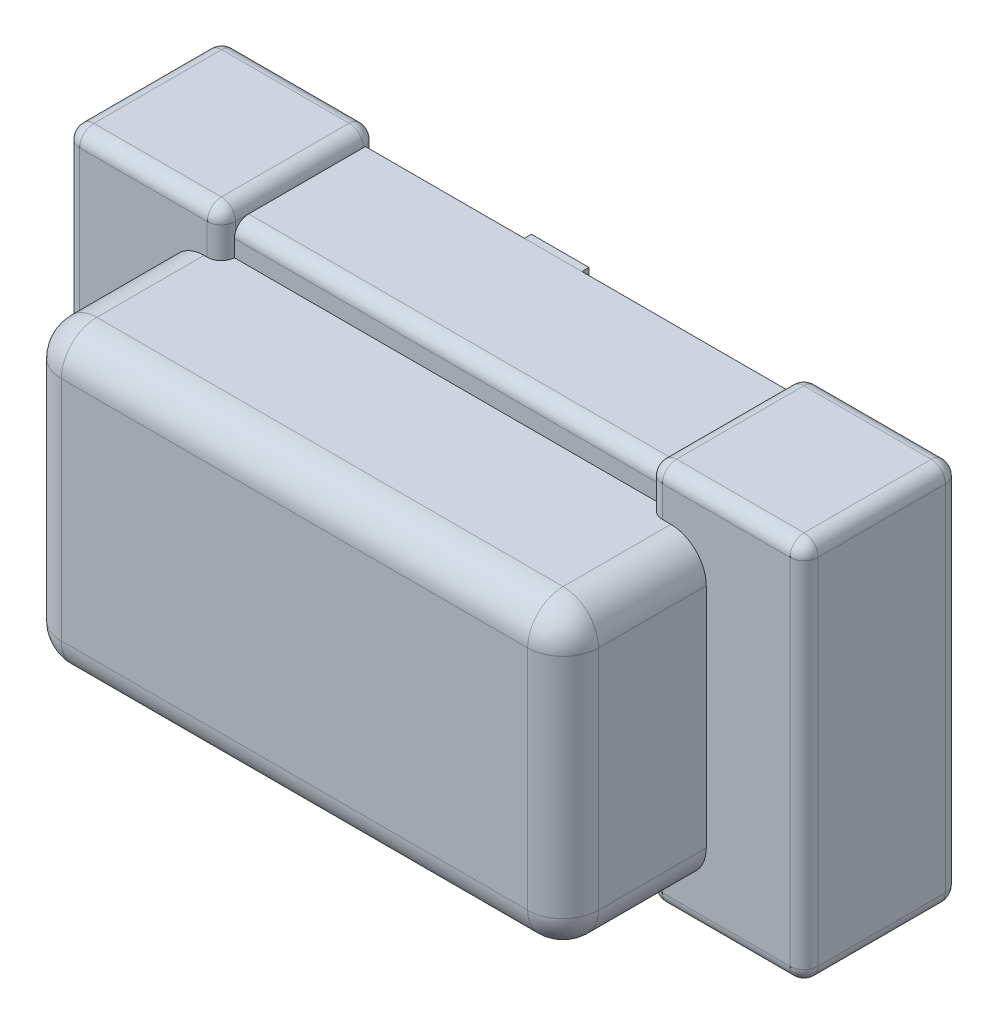
SolidWorks part; units mm, degrees
other "body"
other "bottom"
other "left"
other "right"
other "light"
ref_plane "Front Plane" through (0, 0, 0) normal (0, 0, 1) x (1, 0, 0)
ref_plane "Top Plane" through (0, 0, 0) normal (0, 1, 0) x (1, 0, 0)
ref_plane "Right Plane" through (0, 0, 0) normal (1, 0, 0) x (0, 0, -1)
sketch "Sketch3" plane through (0, 0, 0) normal (0, 0, 1) x (1, 0, 0)
  line L1 (0, 0) -> (1, 0)
  line L2 (0, 0) -> (0, 0.5)
  line L3 (0, 0.5) -> (1, 0.5)
  line L4 (1, 0) -> (1, 0.5)
  dimension "D1" = 1
  dimension "D2" = 0.5
extrude "Boss-Extrude1" add sketch "Sketch3" along normal blind 0.1848
sketch "Sketch4" plane through (0, 0, 0) normal (0, 1, 0) x (1, 0, 0)
  line L1 (-0.022, -0.2033) -> (0.198, -0.2033)
  line L2 (-0.022, -0.2033) -> (-0.022, 0.017)
  line L3 (-0.022, 0.017) -> (0.198, 0.017)
  line L4 (0.198, -0.2033) -> (0.198, 0.017)
  line L5 (1.02, -0.2026) -> (0.8, -0.2026)
  line L6 (1.02, -0.2026) -> (1.02, 0.017)
  line L7 (1.02, 0.017) -> (0.8, 0.017)
  line L8 (0.8, -0.2026) -> (0.8, 0.017)
  dimension "D1" = 0.22
  dimension "D2" = 0.22
  dimension "D3" = 0.2203
  dimension "D4" = 0.2196
sketch "Sketch6" plane through (0, 0, 0) normal (0, 0, -1) x (-1, 0, 0)
  line L0 (0, 0) -> (-1, 0) construction
  line L1 (-0.4224, 0) -> (-0.5037, 0)
  line L2 (-0.4224, 0) -> (-0.4224, 0.5)
  line L3 (-0.4224, 0.5) -> (-0.5037, 0.5)
  line L4 (-0.5037, 0) -> (-0.5037, 0.5)
  line L5 (-1, 0.5) -> (0, 0.5) construction
  line L7 (-0.5037, 0.1333) -> (-0.5755, 0.1333)
  line L8 (-0.5037, 0.1333) -> (-0.5037, 0.3475)
  line L9 (-0.5037, 0.3475) -> (-0.5755, 0.3475)
  line L10 (-0.5755, 0.1333) -> (-0.5755, 0.3475)
  line M2 (-1, 0) -> (0, 0)
  line M4 (0, 0.5) -> (-1, 0.5)
extrude "Boss-Extrude5" add sketch "Sketch6" along normal blind 0.01 separate body contours L4 L2 M2 M4 | L10 L7 L4 L9
extrude "Boss-Extrude9" add sketch "Sketch4" along normal blind 0.52 and the other way blind 0.02 separate body
sketch "Sketch7" plane through (0, 0, 0.1848) normal (0, 0, 1) x (1, 0, 0)
  line L1 (0.882, 0.0356) -> (0.1235, 0.0356)
  line L2 (0.882, 0.0356) -> (0.882, 0.4563)
  line L3 (0.882, 0.4563) -> (0.1235, 0.4563)
  line L4 (0.1235, 0.0356) -> (0.1235, 0.4563)
extrude "Boss-Extrude10" add sketch "Sketch7" along normal blind 0.22 separate body
fillet "Fillet4" radius 0.05 8 edges at (0.882, 0.0356, 0.2948) (0.1235, 0.0356, 0.2948) (0.5027, 0.4563, 0.4048) (0.882, 0.4563, 0.2948) (0.1235, 0.4563, 0.2948) (0.1235, 0.246, 0.4048) (0.882, 0.246, 0.4048) (0.5027, 0.0356, 0.4048)
fillet "Fillet7" radius 0.02 12 edges at (0.91, -0.02, -0.017) (1.02, -0.02, 0.0928) (1.02, 0.25, -0.017) (0.91, -0.02, 0.2026) (1.02, 0.25, 0.2026) (0.91, 0.52, 0.2026) (0.91, 0.52, -0.017) (1.02, 0.52, 0.0928) (0.8, -0.02, 0.0928) (0.8, 0.25, -0.017) (0.8, 0.52, 0.0928) (0.8, 0.25, 0.2026)
fillet "Fillet8" radius 0.02 12 edges at (0.198, 0.25, 0.2033) (0.088, -0.02, 0.2033) (0.198, -0.02, 0.0932) (0.198, 0.52, 0.0932) (0.088, 0.52, 0.2033) (-0.022, -0.02, 0.0932) (-0.022, 0.52, 0.0932) (-0.022, 0.25, 0.2033) (0.088, -0.02, -0.017) (0.198, 0.25, -0.017) (0.088, 0.52, -0.017) (-0.022, 0.25, -0.017)
fillet "Fillet9" radius 0.02 2 edges at (0.5, 0.5, 0.1848) (0.5, 0, 0.1848)
